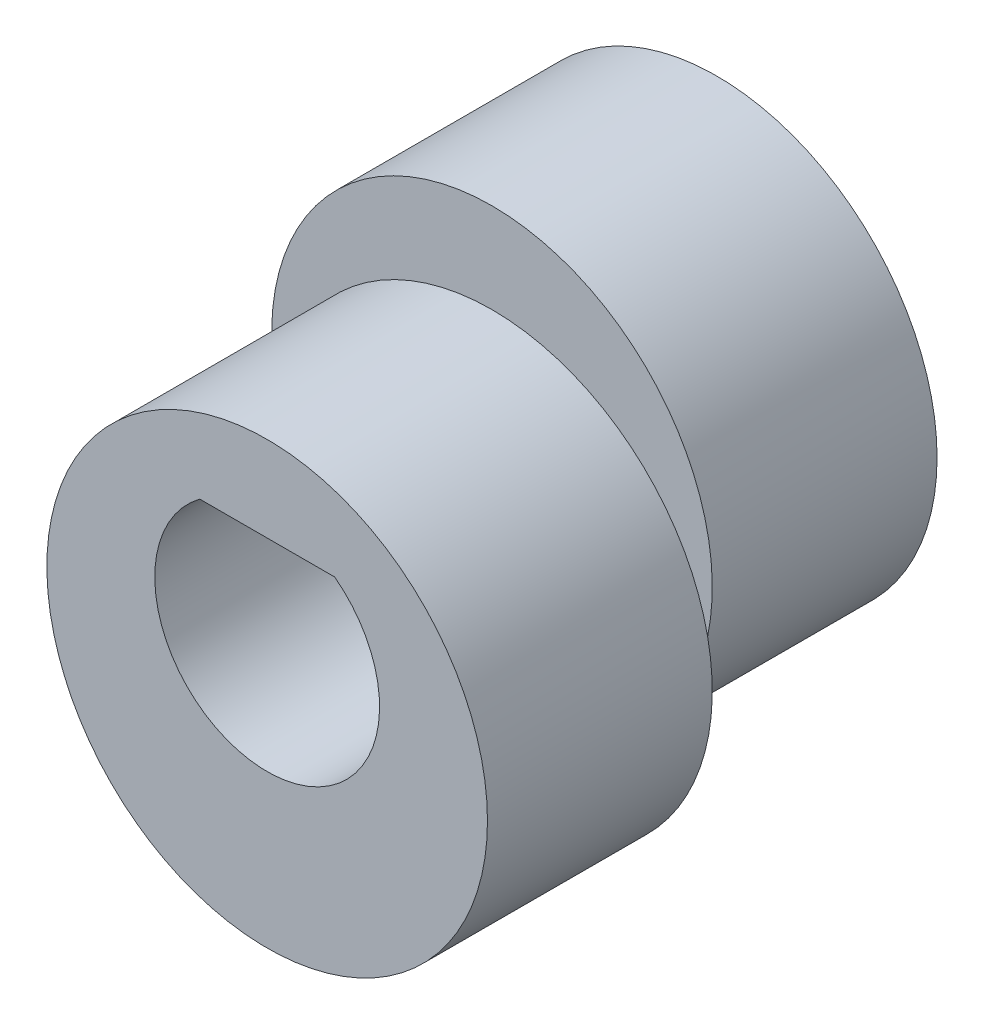
SolidWorks part; units mm, degrees
ref_plane "Plan de face" through (0, 0, 0) normal (0, 0, 1) x (1, 0, 0)
ref_plane "Plan de dessus" through (0, 0, 0) normal (0, 1, 0) x (1, 0, 0)
ref_plane "Plan de droite" through (0, 0, 0) normal (1, 0, 0) x (0, 0, -1)
sketch "Esquisse1" plane through (0, 0, 0) normal (0, 0, 1) x (1, 0, 0)
  line L0 (-1.5, 2) -> (1.5, 2)
  arc A0 (-1.5, 2) -> (1.5, 2) centre (0, 0) ccw
  circle A2 centre (0, 1) radius 4.9
  dimension "D1" = 2.5
  dimension "D2" = 2
  dimension "D4" = 9.8
  dimension "D5" = 1
extrude "Boss.-Extru.1" add sketch "Esquisse1" along normal blind 5
sketch "Esquisse2" plane through (0, 0, 5) normal (0, 0, 1) x (1, 0, 0)
  line L0 (-1.5, 2) -> (1.5, 2)
  arc A0 (-1.5, 2) -> (1.5, 2) centre (0, 0) ccw
  circle A1 centre (0, -1) radius 4.9
  dimension "D1" = 9.8
  dimension "D2" = 1
extrude "Boss.-Extru.2" add sketch "Esquisse2" along normal blind 5
